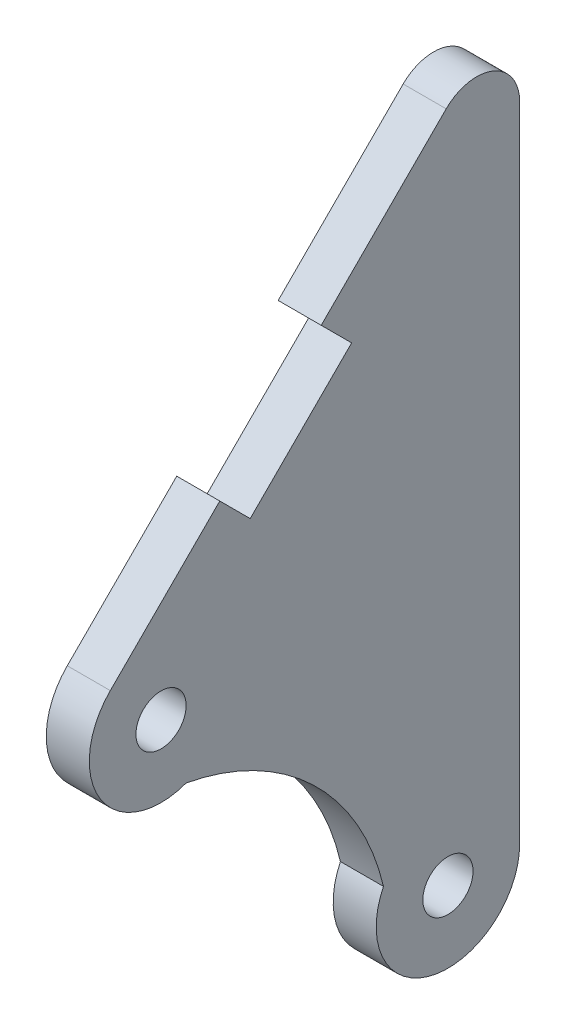
SolidWorks part; units mm, degrees
ref_plane "Alzado" through (0, 0, 0) normal (0, 0, 1) x (1, 0, 0)
ref_plane "Planta" through (0, 0, 0) normal (0, 1, 0) x (1, 0, 0)
ref_plane "Vista lateral" through (0, 0, 0) normal (1, 0, 0) x (0, 0, -1)
sketch "Croquis1" plane through (0, 0, 0) normal (1, 0, 0) x (0, 0, -1)
  line L0 (0, 0) -> (0, 20) construction
  line L1 (-15, 30) -> (15, 30) construction
  line L2 (-10, 30) -> (-20, 20) construction
  line L3 (0, 0) -> (-20, 20) construction
  line L4 (10, 5) -> (18.1246, 5) construction
  line L5 (-25, 20) -> (-25, 30) construction
  line L6 (-25, 30) -> (-15, 30) construction
  line L7 (5, 0) -> (5, 5) construction
  line L8 (5, 5) -> (10, 5) construction
  line L9 (18.1246, 5) -> (18.1246, 10) construction
  line L10 (0, 20) -> (-20, 20) construction
  line L11 (15, 30) -> (15, 55) construction
  line L12 (18.1246, 10) -> (15, 10) construction
  line L13 (15, 10) -> (15, 20) construction
  line L14 (15, 20) -> (18.1246, 20) construction
  line L15 (18.1246, 20) -> (18.1246, 25) construction
  line L16 (18.1246, 25) -> (15, 25) construction
  line L17 (15, 25) -> (15, 30) construction
  line L18 (-20, 20) -> (15, 55) construction
  line L19 (-20, 20) -> (-23.5355, 23.5355) construction
  line L20 (-23.5355, 23.5355) -> (15, 62.0711) construction
  line L21 (15, 62.0711) -> (15, 55) construction
  line L22 (12.0711, 55) -> (10, 57.0711) construction
  line L23 (-23.5355, 23.5355) -> (-15.9049, 31.1661)
  line L24 (5, 5) -> (5, 52.0711) construction
  line L25 (5, 44.8284) -> (5, 0)
  line L28 (-13.7836, 29.0448) -> (-6.7126, 36.1159)
  line L29 (-13.7836, 29.0448) -> (-15.9049, 31.1661)
  line L30 (-6.7126, 36.1159) -> (-8.8339, 38.2372)
  line L31 (-8.8339, 38.2372) -> (-0.1213, 46.9497)
  arc A0 (-4.4934, 2.1929) -> (5, 0) centre (0, 0) ccw
  arc A2 (-18.2558, 15.3141) -> (-4.4934, 2.1929) centre (-21.4473, -1.8114) cw
  arc A3 (-25, 20) -> (-15, 30) centre (-15, 20) cw construction
  arc A4 (5, 0) -> (10, 5) centre (10, 0) cw construction
  circle A5 centre (0, 0) radius 1.75
  circle A6 centre (-20, 20) radius 1.75
  arc A7 (-23.5355, 23.5355) -> (-18.2558, 15.3141) centre (-20, 20) ccw
  arc A8 (5, 44.8284) -> (-0.1213, 46.9497) centre (2, 44.8284) ccw
  arc A10 (-23.5355, 23.5355) -> (-18.2558, 15.3141) centre (-20, 20) ccw construction
  arc A11 (-4.4934, 2.1929) -> (5, 0) centre (0, 0) ccw construction
  point P42 (-12.3694, 34.7017)
  dimension "D1" = 3.5
  dimension "D5" = 5
  dimension "D2" = 20
  dimension "D4" = 3
  dimension "D3" = 33.1127
  dimension "D8" = 0
extrude "Saliente-Extruir1" add sketch "Croquis1" along normal blind 3
